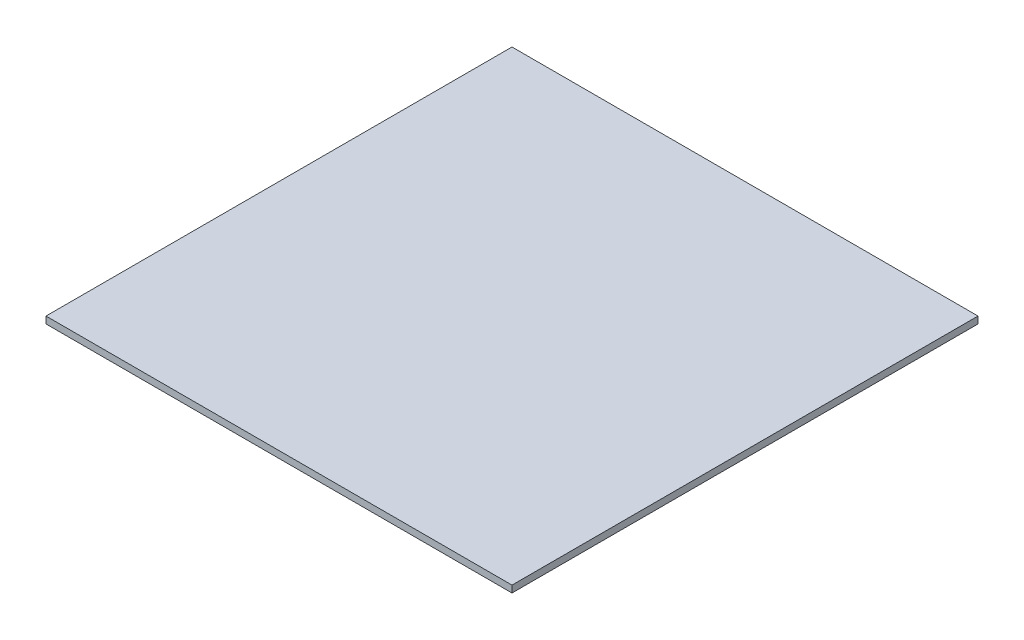
SolidWorks part; units mm, degrees
material "TRIPLAY"
ref_plane "Alzado" through (0, 0, 0) normal (0, 0, 1) x (1, 0, 0)
ref_plane "Planta" through (0, 0, 0) normal (0, 1, 0) x (1, 0, 0)
ref_plane "Vista lateral" through (0, 0, 0) normal (1, 0, 0) x (0, 0, -1)
sketch "Croquis1" plane through (0, 0, 0) normal (0, 1, 0) x (1, 0, 0)
  line L1 (-305, 305) -> (305, 305)
  line L2 (-305, 305) -> (-305, -305)
  line L3 (-305, -305) -> (305, -305)
  line L4 (305, 305) -> (305, -305)
  line L5 (-305, 305) -> (305, -305) construction
  line L6 (-305, -305) -> (305, 305) construction
  point P0 (0, 0)
  dimension "D1" = 610
extrude "Saliente-Extruir1" add sketch "Croquis1" along normal blind 9
